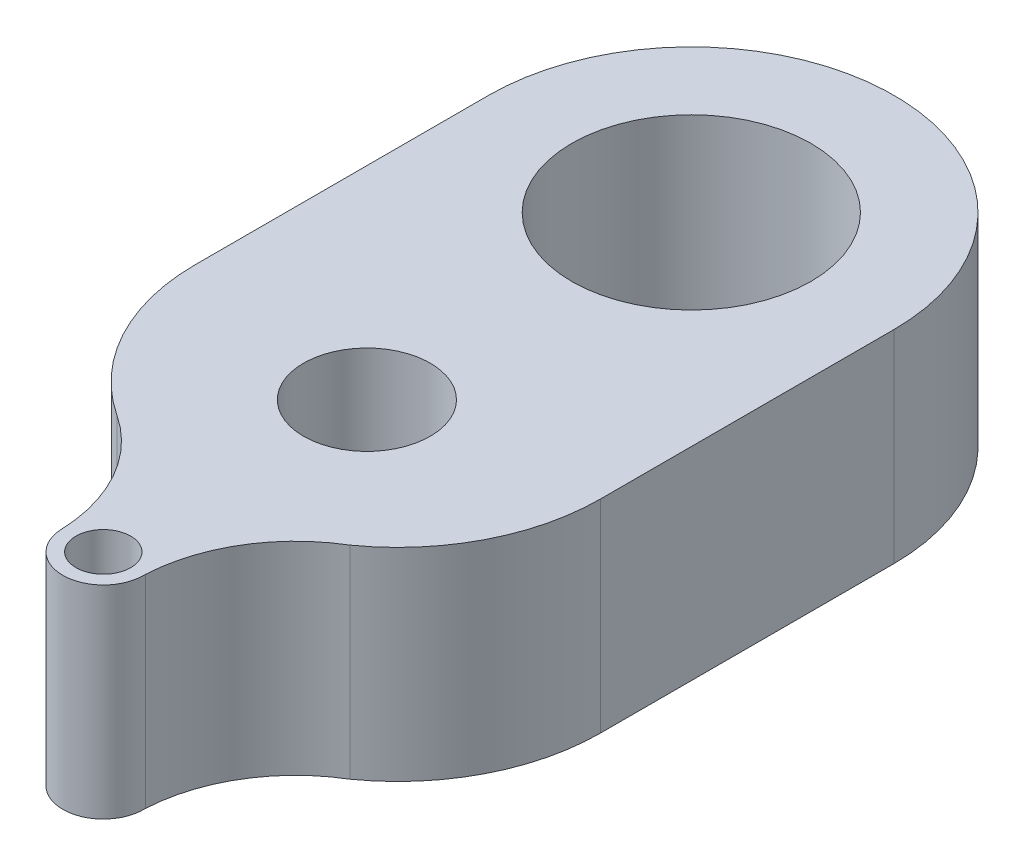
SolidWorks part; units mm, degrees
ref_plane "Front" through (0, 0, 0) normal (0, 0, 1) x (1, 0, 0)
ref_plane "Top" through (0, 0, 0) normal (0, 1, 0) x (1, 0, 0)
ref_plane "Right" through (0, 0, 0) normal (1, 0, 0) x (0, 0, -1)
sketch "Sketch1" plane through (0, 0, 0) normal (0, 1, 0) x (1, 0, 0)
  line L1 (0, 0) -> (0, 5.8175) construction
  line B0 (-1.27, 0) -> (-1.27, -1.8385)
  line B1 (0, -3.683) -> (0.2538, -3.674) construction
  line B2 (0, -3.937) -> (0, 0) construction
  line B3 (1.27, 0) -> (1.27, -1.8385)
  line B4 (0.2538, -3.674) -> (-0.2538, -3.692) construction
  arc B5 (1.27, -1.8385) -> (0.7353, -2.874) centre (0, -1.8385) cw
  arc B6 (0.7353, -2.874) -> (0.2538, -3.674) centre (1.2447, -3.7254) ccw
  arc B7 (1.27, 0) -> (-1.27, 0) centre (0, 0) ccw
  circle B8 centre (0, -3.683) radius 0.1715
  circle B9 centre (0, -3.683) radius 0.254
  arc B10 (-1.27, -1.8385) -> (-0.6992, -2.8987) centre (0, -1.8385) ccw
  circle B11 centre (0, 0) radius 0.7493
  arc B12 (-0.6992, -2.8987) -> (-0.2538, -3.692) centre (-1.2454, -3.727) cw
  circle B13 centre (0, -2.032) radius 0.3969
  circle B14 centre (0, 0) radius 1.2192 construction
sketch_block_instance "Block1-1"
sketch_block "Block1" parameters "D3"=0.9922, "D4"=0.3429, "D5"=0.508, "D7"=1.4986, "D8"=0.7937, "D11"=2.4384, "D2"=0.254, "D6"=2.54, "D9"=1.651, "D10"=2.032, "D1"=180
extrude "Boss-Extrude1" add sketch "Sketch1" along normal blind 1.27 contours B10 B12 B9 B6 B5 B3 B7 B0 B13 B11 | B9 B8
sketch "Sketch2" plane through (0, 1.27, 0) normal (0, 1, 0) x (1, 0, 0)
  line L0 (1.27, 0) -> (1.27, -1.8385) construction
  line L1 (3.81, 3.81) -> (-46.99, 3.81)
  line L2 (3.81, 3.81) -> (3.81, -27.94)
  line L3 (3.81, -27.94) -> (-46.99, -27.94)
  line L4 (-46.99, 3.81) -> (-46.99, -27.94)
  arc A0 (1.27, 0) -> (-1.27, 0) centre (0, 0) ccw construction
  point P9 (0, 1.27)
  dimension "D1" = 2.54
  dimension "D2" = 2.54
  dimension "D3" = 50.8
  dimension "D4" = 31.75
